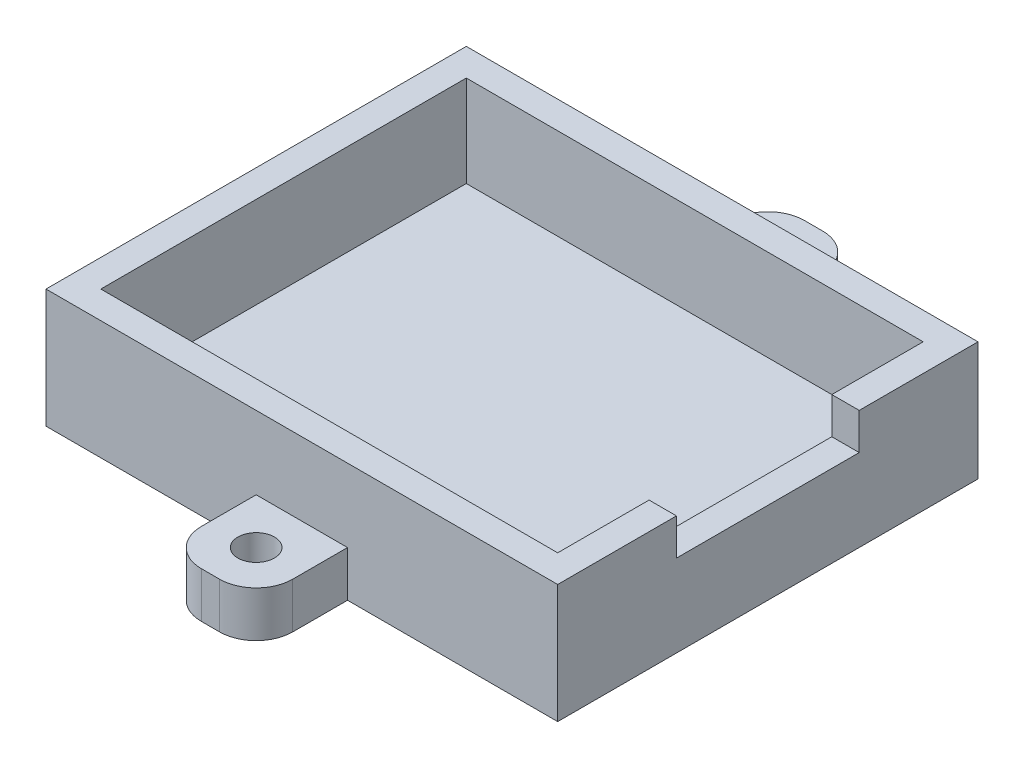
SolidWorks part; units mm, degrees
ref_plane "前视基准面" through (0, 0, 0) normal (0, 0, 1) x (1, 0, 0)
ref_plane "上视基准面" through (0, 0, 0) normal (0, 1, 0) x (1, 0, 0)
ref_plane "右视基准面" through (0, 0, 0) normal (1, 0, 0) x (0, 0, -1)
sketch "草图1" plane through (0, 0, 0) normal (0, 1, 0) x (1, 0, 0)
  line L1 (0, 0) -> (28, 0)
  line L2 (0, 0) -> (0, -23)
  line L3 (0, -23) -> (28, -23)
  line L4 (28, 0) -> (28, -23)
  dimension "D1" = 28
  dimension "D2" = 23
extrude "凸台-拉伸1" add sketch "草图1" along normal blind 1.5
sketch "草图2" plane through (0, 1.5, 0) normal (0, 1, 0) x (1, 0, 0)
  line L0 (1.5, -21.5) -> (1.5, -1.5)
  line L1 (0, -23) -> (28, -23)
  line L2 (0, -23) -> (0, 0)
  line L3 (0, 0) -> (28, 0)
  line L4 (28, -23) -> (28, 0)
  line L5 (1.5, -1.5) -> (26.5, -1.5)
  line L6 (26.5, -21.5) -> (26.5, -1.5)
  line L7 (1.5, -21.5) -> (26.5, -21.5)
  dimension "D1" = 1.5
extrude "凸台-拉伸2" add sketch "草图2" along normal blind 5
sketch "草图4" plane through (28, 0, 0) normal (1, 0, 0) x (0, 0, -1)
  line L0 (-23, 6.5) -> (0, 6.5) construction
  line L1 (-16.5, 6.5) -> (-6.5, 6.5)
  line L2 (-16.5, 6.5) -> (-16.5, 4.5)
  line L3 (-16.5, 4.5) -> (-6.5, 4.5)
  line L4 (-6.5, 6.5) -> (-6.5, 4.5)
  line L5 (-23, 6.5) -> (-23, 0) construction
  point P8 (-18.4733, 3.8712)
  dimension "D1" = 10
  dimension "D2" = 2
  dimension "D3" = 6.5
extrude "切除-拉伸1" cut sketch "草图4" against normal blind 2
sketch "草图5" plane through (0, 0, 0) normal (0, -1, 0) x (1, 0, 0)
  line L0 (28, 0) -> (0, 0) construction
  line L1 (11.5, 28) -> (16.5, 28)
  line L2 (11.5, 28) -> (11.5, -5)
  line L3 (11.5, -5) -> (16.5, -5)
  line L4 (16.5, 28) -> (16.5, -5)
  line L5 (0, 0) -> (0, 23) construction
  dimension "D1" = 5
  dimension "D2" = 33
  dimension "D3" = 5
  dimension "D4" = 11.5
extrude "凸台-拉伸3" add sketch "草图5" against normal blind 2.5
sketch "草图6" plane through (0, 2.5, 0) normal (0, 1, 0) x (1, 0, 0)
  line L0 (11.5, -1.5) -> (16.5, -1.5) construction
  line L1 (16.5, -21.5) -> (11.5, -21.5)
  line L2 (16.5, -21.5) -> (16.5, -1.5)
  line L3 (16.5, -1.5) -> (11.5, -1.5)
  line L4 (11.5, -21.5) -> (11.5, -1.5)
  line L5 (11.5, -21.5) -> (11.5, -1.5) construction
extrude "切除-拉伸2" cut sketch "草图6" against normal blind 1
sketch "草图7" plane through (0, 2.5, 0) normal (0, 1, 0) x (1, 0, 0)
  circle A0 centre (14, 2.5) radius 1
  circle A1 centre (14, -25.5) radius 1
  dimension "D1" = 2
  dimension "D2" = 2
extrude "切除-拉伸3" cut sketch "草图7" against normal through all
fillet "圆角1" radius 2 4 edges at (16.5, 1.25, -5) (11.5, 1.25, -5) (16.5, 1.25, 28) (11.5, 1.25, 28)
